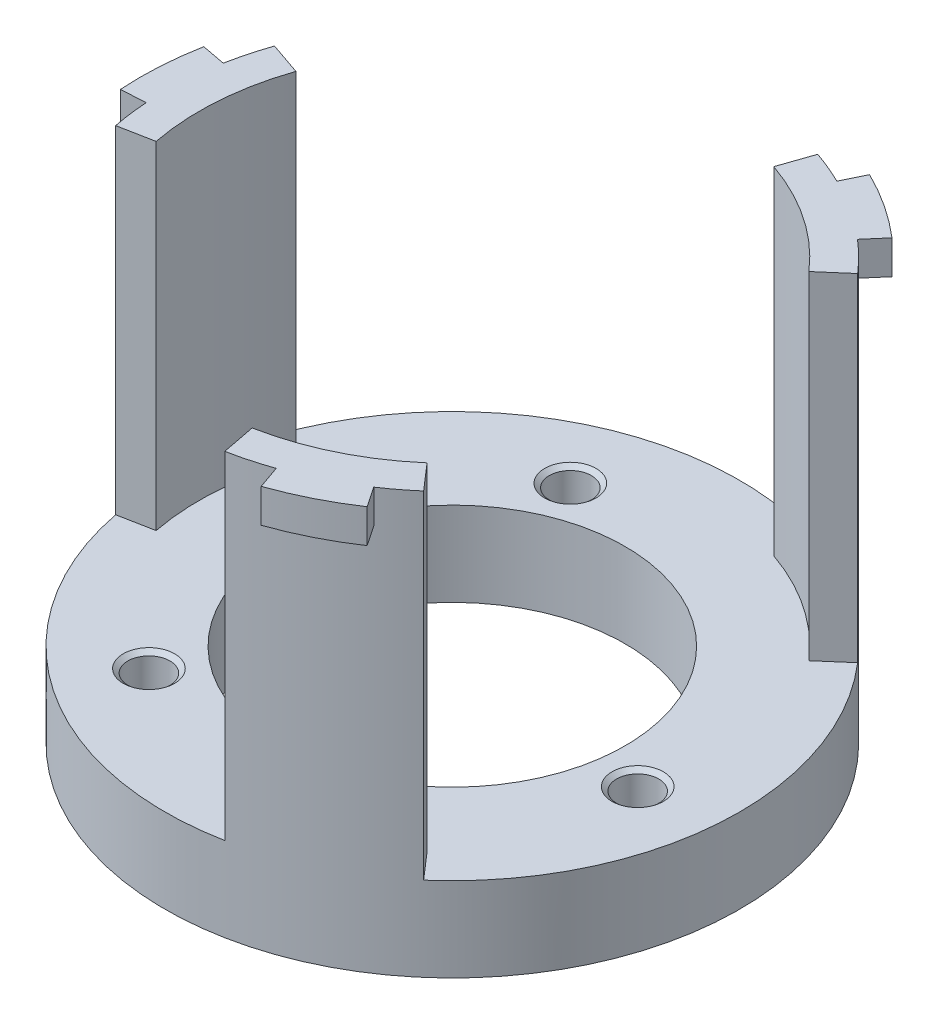
SolidWorks part; units mm, degrees
ref_plane "前基準面" through (0, 0, 0) normal (0, 0, 1) x (1, 0, 0)
ref_plane "上基準面" through (0, 0, 0) normal (0, 1, 0) x (1, 0, 0)
ref_plane "右基準面" through (0, 0, 0) normal (1, 0, 0) x (0, 0, -1)
sketch "草圖1" plane through (0, 0, 0) normal (0, 1, 0) x (1, 0, 0)
  line L1 (-30.3038, 12.448) -> (30.3038, 12.448)
  line L2 (-30.3038, 12.448) -> (-30.3038, -12.448)
  line L3 (-30.3038, -12.448) -> (30.3038, -12.448)
  line L4 (30.3038, 12.448) -> (30.3038, -12.448)
  line L5 (-30.3038, 12.448) -> (30.3038, -12.448) construction
  line L6 (-30.3038, -12.448) -> (30.3038, 12.448) construction
  point P0 (0, 0)
extrude "填料-伸長1" add sketch "草圖1" along normal blind 13.8
sketch "草圖2" plane through (0, 0, 12.448) normal (0, 0, 1) x (1, 0, 0)
  line L6 (11.75, 12.75) -> (24.25, 12.75)
  line L7 (11.75, 12.75) -> (11.75, 2.25)
  line L8 (11.75, 2.25) -> (24.25, 2.25)
  line L9 (24.25, 12.75) -> (24.25, 2.25)
  line L10 (11.75, 12.75) -> (24.25, 2.25) construction
  line L11 (11.75, 2.25) -> (24.25, 12.75) construction
  point P10 (18, 7.5)
  dimension "D1" = 10.5
  dimension "D2" = 12.5
extrude "除料-伸長1" cut sketch "草圖2" against normal through all
sketch "草圖3" plane through (0, 0, 12.448) normal (0, 0, 1) x (1, 0, 0)
  line L0 (24.25, 2.25) -> (24.25, 12.75) construction
  line L1 (11.75, 12.75) -> (24.25, 12.75)
  line L2 (11.75, 12.75) -> (11.75, 2.25)
  line L3 (11.75, 2.25) -> (24.25, 2.25)
  line L4 (24.25, 12.75) -> (24.25, 2.25)
  line L5 (11.75, 12.75) -> (24.25, 2.25) construction
  line L6 (11.75, 2.25) -> (24.25, 12.75) construction
  line L7 (11.75, 2.25) -> (24.25, 2.25) construction
  point P0 (18, 7.5)
extrude "填料-伸長2" add sketch "草圖3" against normal blind 0.5
sketch "草圖4" plane through (0, 0, 11.948) normal (0, 0, -1) x (-1, 0, 0)
  circle A0 centre (-18, 7.5) radius 2
extrude "除料-伸長2" cut sketch "草圖4" against normal through all
sketch "草圖5" plane through (0, 0, 12.448) normal (0, 0, 1) x (1, 0, 0)
  circle A0 centre (-15.1519, 6.9) radius 2.975
extrude "填料-伸長3" add sketch "草圖5" along normal blind 7.5
sketch "草圖10" plane through (0, 13.8, 0) normal (0, 1, 0) x (1, 0, 0)
  line L5 (-5.2158, 10.2392) -> (5.2158, 10.2392)
  line L6 (-5.2158, 10.2392) -> (-5.2158, -1.2175)
  line L7 (-5.2158, -1.2175) -> (5.2158, -1.2175)
  line L8 (5.2158, 10.2392) -> (5.2158, -1.2175)
  line L9 (-5.2158, 10.2392) -> (5.2158, -1.2175) construction
  line L10 (-5.2158, -1.2175) -> (5.2158, 10.2392) construction
  point P0 (0, 4.5109)
extrude "填料-伸長4" add sketch "草圖10" along normal blind 6.5
hole_wizard "M3 螺紋孔3" positions "草圖11" profile "草圖12" tap size "M3" standard "ISO"
sketch "草圖11" plane through (0, 20.3, 0) normal (0, 1, 0) x (1, 0, 0)
  line L0 (0, 0.8327) -> (0, 8.1327)
  point P0 (0, 0.8327)
  dimension "D1" = 7.3
sketch "草圖12" plane through (0, 20.3, -0.8327) normal (1, 0, 0) x (0, 0, 1)
  line L0 (0, 0) -> (0, 20.3)
  line L1 (0, 20.3) -> (1.25, 20.3)
  line L2 (1.25, 20.3) -> (1.25, 0.2308)
  line L3 (1.25, 0.2308) -> (1.525, 0)
  line L5 (1.525, 0) -> (0, 0)
  line L6 (-1.25, 0.2308) -> (-1.525, 0) construction
  line L11 (0, -6.35) -> (0, 107.95) construction
  dimension "貫穿螺孔鑽直徑" = 2.5
  dimension "貫穿螺孔鑽深度" = 20.3
  dimension "近端錐孔直徑" = 3.05
  dimension "近端錐孔角度" = 100
cosmetic thread "鑽孔螺紋3" parameters "D2"=3
cosmetic thread "鑽孔螺紋4" parameters "D2"=3
cosmetic thread "鑽孔螺紋5" parameters "D2"=3
sketch "草圖14" plane through (0, 0, 12.448) normal (0, 0, 1) x (1, 0, 0)
  circle A0 centre (18, 7.5) radius 2.8505
  circle A1 centre (18, 7.5) radius 2
extrude "填料-伸長5" add sketch "草圖14" along normal blind 1.5
fillet "圓角1" radius 3 1 edges at (-30.3038, 6.9, -12.448)
fillet "圓角2" radius 3 1 edges at (-30.3038, 6.9, 12.448)
fillet "圓角3" radius 3 1 edges at (30.3038, 6.9, -12.448)
fillet "圓角4" radius 3 1 edges at (30.3038, 6.9, 12.448)
sketch "草圖16" plane through (0, 0, 0) normal (0, -1, 0) x (1, 0, 0)
  circle A0 centre (-17.1174, 0) radius 5.5
  circle A1 centre (-17.1174, 0) radius 7.5
extrude "填料-伸長6" add sketch "草圖16" along normal blind 15
sketch "草圖17" plane through (0, -15, 0) normal (0, -1, 0) x (1, 0, 0)
  circle A0 centre (-17.1174, 0) radius 9.15
  circle A1 centre (-17.1174, 0) radius 17.05
extrude "填料-伸長7" add sketch "草圖17" along normal blind 5 separate body
sketch "草圖18" plane through (0, -15, 0) normal (0, 1, 0) x (1, 0, 0)
  circle A0 centre (-17.1174, 0) radius 10.2514
extrude "填料-伸長8" add sketch "草圖18" along normal blind 15
sketch "草圖20" plane through (0, -20, 0) normal (0, -1, 0) x (1, 0, 0)
  line L1 (-27.7874, 1.565) -> (-27.7874, -1.565)
  line L2 (-27.7874, 1.565) -> (-26.1326, 1.565)
  line L3 (-27.7874, -1.565) -> (-26.1326, -1.565)
  line L4 (-26.1326, 1.565) -> (-26.1326, -1.565)
  circle A0 centre (-17.1174, 0) radius 9.15 construction
  point P7 (-27.7874, 0)
extrude "除料-伸長4" cut sketch "草圖20" against normal through all
sketch "草圖21" plane through (0, -15, 0) normal (0, -1, 0) x (1, 0, 0)
  line L0 (-26.1326, 1.565) -> (-25.7373, 1.565)
  line L1 (-26.1326, -1.565) -> (-25.7373, -1.565)
  line L2 (-25.7373, -1.565) -> (-25.7373, 1.565)
  line L3 (-26.1326, 1.565) -> (-26.1326, -1.565)
extrude "除料-伸長5" cut sketch "草圖21" against normal blind 10
sketch "草圖22" plane through (0, 0, 0) normal (0, -1, 0) x (1, 0, 0)
  line L1 (-32.2696, 20.7097) -> (32.2696, 20.7097)
  line L2 (-32.2696, 20.7097) -> (-32.2696, -20.7097)
  line L3 (-32.2696, -20.7097) -> (32.2696, -20.7097)
  line L4 (32.2696, 20.7097) -> (32.2696, -20.7097)
  line L5 (-32.2696, 20.7097) -> (32.2696, -20.7097) construction
  line L6 (-32.2696, -20.7097) -> (32.2696, 20.7097) construction
  point P0 (0, 0)
extrude "除料-伸長6" cut sketch "草圖22" against normal through all
hole_wizard "M3 螺紋孔4" positions "草圖31" profile "草圖32" tap size "M3" standard "ISO"
sketch "草圖31" plane through (0, -15, 0) normal (0, 1, 0) x (1, 0, 0)
  point P0 (-24.9648, -10.1554)
  point P7 (-21.9886, 11.8737)
  point P8 (-4.3989, -1.7183)
  dimension "D1" = 3
sketch "草圖32" plane through (-24.9648, -15, 10.1554) normal (1, 0, 0) x (0, 0, 1)
  line L0 (0, 0) -> (0, 5)
  line L1 (0, 5) -> (1.25, 5)
  line L2 (1.25, 5) -> (1.25, 0.2308)
  line L3 (1.25, 0.2308) -> (1.525, 0)
  line L5 (1.525, 0) -> (0, 0)
  line L6 (-1.25, 0.2308) -> (-1.525, 0) construction
  line L11 (0, -6.35) -> (0, 107.95) construction
  dimension "貫穿螺孔鑽直徑" = 2.5
  dimension "貫穿螺孔鑽深度" = 5
  dimension "近端錐孔直徑" = 3.05
  dimension "近端錐孔角度" = 100
cosmetic thread "鑽孔螺紋6" parameters "D2"=3
cosmetic thread "鑽孔螺紋7" parameters "D2"=3
cosmetic thread "鑽孔螺紋8" parameters "D2"=3
sketch "草圖39" plane through (0, 0, 0) normal (0, 1, 0) x (1, 0, 0)
  circle A0 centre (-17.1174, 0) radius 10.2514
extrude "除料-伸長14" cut sketch "草圖39" against normal through all
sketch "草圖40" plane through (0, -15, 0) normal (0, 1, 0) x (1, 0, 0)
  line L2 (-33.2336, 5.5652) -> (-31.2959, 4.896)
  line L3 (-33.857, -3.2385) -> (-31.8444, -2.8491)
  line L4 (-11.5523, 16.1162) -> (-12.2214, 14.1785)
  line L5 (-4.2398, 11.1744) -> (-5.7881, 9.8309)
  line L6 (-5.943, -12.8777) -> (-7.2866, -11.3293)
  line L7 (-13.8789, -16.7396) -> (-14.2683, -14.7269)
  line L8 (-35.8403, 3.2334) -> (-33.9187, 2.9015)
  line L9 (-36.0963, -0.8956) -> (-34.1485, -0.8037)
  arc A2 (-33.857, -3.2385) -> (-33.2336, 5.5652) centre (-17.1174, 0) cw
  arc A4 (-31.8444, -2.8491) -> (-31.2959, 4.896) centre (-17.1174, 0) cw
  arc A5 (-12.2214, 14.1785) -> (-5.7881, 9.8309) centre (-17.1174, 0) cw
  arc A6 (-11.5523, 16.1162) -> (-4.2398, 11.1744) centre (-17.1174, 0) cw
  arc A7 (-7.2866, -11.3293) -> (-14.2683, -14.7269) centre (-17.1174, 0) cw
  arc A8 (-5.943, -12.8777) -> (-13.8789, -16.7396) centre (-17.1174, 0) cw
  arc A10 (-36.0963, -0.8956) -> (-35.8403, 3.2334) centre (-17.1174, 0) cw
  point P16 (-17.1174, 0)
  circle M7 centre (-17.1174, 0) radius 17.05
  dimension "D1" = 3
extrude "填料-伸長10" add sketch "草圖40" along normal blind 20 contours L4 A5 L5 M7 | L6 A7 L7 M7 | L2 A4 L3 A2
sketch "草圖41" plane through (0, -15, 0) normal (0, 1, 0) x (1, 0, 0)
  line L0 (-11.0001, -17.4593) -> (-11.4796, -16.0909)
  line L1 (-6.8108, -15.3631) -> (-7.6187, -14.1589)
  line L2 (-35.2963, 3.4319) -> (-33.8715, 3.1629)
  line L3 (-35.5756, -1.2442) -> (-34.1288, -1.1467)
  line L4 (-5.0559, 14.0274) -> (-6.0012, 12.928)
  line L5 (-8.9659, 16.6073) -> (-9.6048, 15.3057)
  line L6 (-21.9886, 11.8737) -> (-17.1174, 0)
  arc A0 (-11.0001, -17.4593) -> (-6.8108, -15.3631) centre (-17.1174, 0) ccw
  arc A1 (-13.8789, -16.7396) -> (-5.943, -12.8777) centre (-17.1174, 0) ccw construction
  arc A2 (-11.4796, -16.0909) -> (-7.6187, -14.1589) centre (-17.1174, 0) ccw
  arc A3 (-33.8715, 3.1629) -> (-34.1288, -1.1467) centre (-17.1174, 0) ccw
  arc A4 (-35.2963, 3.4319) -> (-35.5756, -1.2442) centre (-17.1174, 0) ccw
  arc A5 (-6.0012, 12.928) -> (-9.6048, 15.3057) centre (-17.1174, 0) ccw
  arc A6 (-5.0559, 14.0274) -> (-8.9659, 16.6073) centre (-17.1174, 0) ccw
  point P23 (-17.1174, 0)
  dimension "D1" = 18.5
  dimension "D2" = 3
sketch "草圖43" plane through (0, 5, 0) normal (0, 1, 0) x (1, 0, 0)
  line L0 (-35.5756, -1.2442) -> (-34.1288, -1.1467) construction
  line L1 (-35.2963, 3.4319) -> (-33.8715, 3.1629)
  line L2 (-35.5756, -1.2442) -> (-34.1288, -1.1467)
  line L3 (-8.9659, 16.6073) -> (-9.6048, 15.3057)
  line L4 (-5.0559, 14.0274) -> (-6.0012, 12.928)
  line L5 (-6.8108, -15.3631) -> (-7.6187, -14.1589)
  line L6 (-11.0001, -17.4593) -> (-11.4796, -16.0909)
  arc A0 (-35.2963, 3.4319) -> (-35.5756, -1.2442) centre (-17.1174, 0) ccw
  arc A1 (-33.8715, 3.1629) -> (-34.1288, -1.1467) centre (-17.1174, 0) ccw
  arc A2 (-5.0559, 14.0274) -> (-8.9659, 16.6073) centre (-17.1174, 0) ccw
  arc A3 (-6.0012, 12.928) -> (-9.6048, 15.3057) centre (-17.1174, 0) ccw
  arc A4 (-11.0001, -17.4593) -> (-6.8108, -15.3631) centre (-17.1174, 0) ccw
  arc A5 (-11.4796, -16.0909) -> (-7.6187, -14.1589) centre (-17.1174, 0) ccw
  point P21 (-17.1174, 0)
  dimension "D1" = 3
extrude "填料-伸長13" add sketch "草圖43" against normal blind 2
